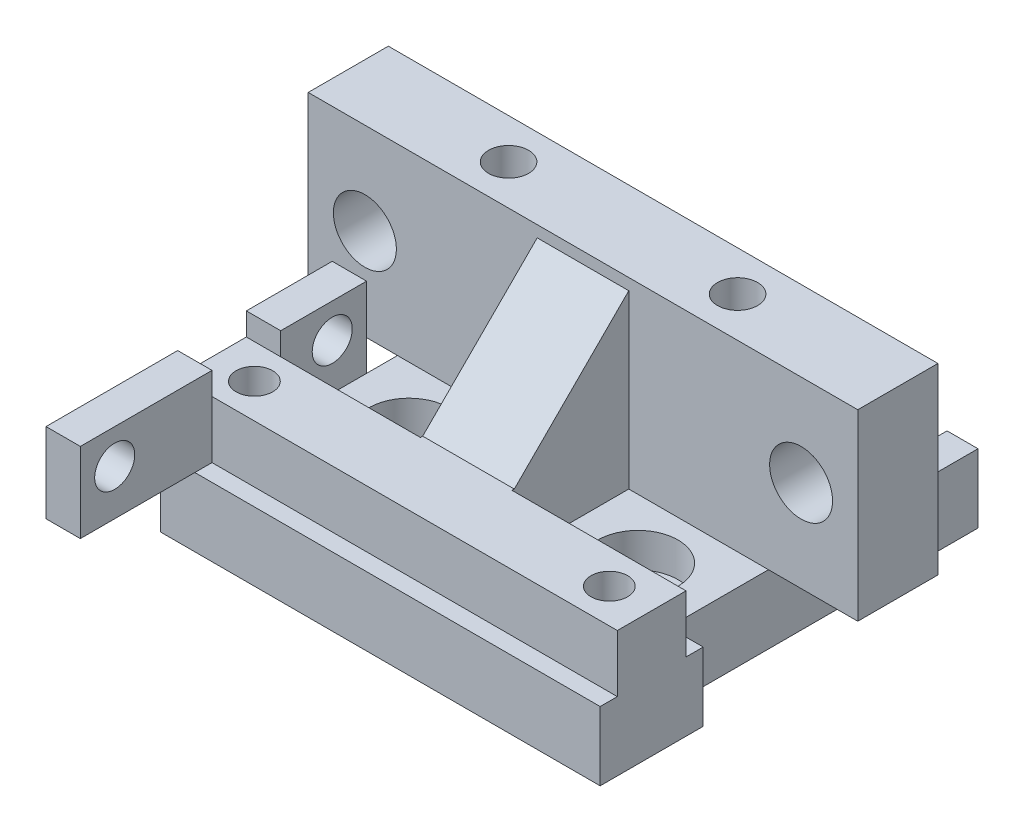
SolidWorks part; units mm, degrees
ref_plane "Спереди" through (0, 0, 0) normal (0, 0, 1) x (1, 0, 0)
ref_plane "Сверху" through (0, 0, 0) normal (0, 1, 0) x (1, 0, 0)
ref_plane "Справа" through (0, 0, 0) normal (1, 0, 0) x (0, 0, -1)
sketch "Эскиз1" plane through (0, 0, 0) normal (0, 1, 0) x (1, 0, 0)
  line L0 (16.2, 27) -> (16.2, 0) construction
  line L2 (0, 0) -> (0, 27)
  line L3 (0, 27) -> (32.4, 27)
  line L4 (32.4, 0) -> (32.4, 27)
  line L5 (0, 13.5) -> (32.4, 13.5) construction
  line L6 (0, 0) -> (-3, 0)
  line L7 (35.4, 0) -> (32.4, 0)
  line L8 (35.4, 0) -> (35.4, -9)
  line L9 (35.4, -9) -> (-3, -9)
  line L10 (-3, 0) -> (-3, -9)
  circle A0 centre (6.2, 23.5) radius 1.6
  circle A1 centre (26.2, 23.5) radius 1.6
  circle A2 centre (6.2, 3.5) radius 1.6
  circle A3 centre (26.2, 3.5) radius 1.6
  circle A4 centre (31.7, -4.5) radius 1.6
  circle A5 centre (0.7, -4.5) radius 1.6
  dimension "D3" = 3.2
  dimension "D6" = 10
  dimension "D12" = 3.2
  dimension "D1" = 32.4
  dimension "D2" = 27
  dimension "D4" = 10
  dimension "D5" = 10
  dimension "D7" = 10
  dimension "D8" = 10
  dimension "D9" = 10
  dimension "D10" = 10
  dimension "D11" = 10
  dimension "D13" = 15.5
  dimension "D14" = 15.5
  dimension "D15" = 8
  dimension "D16" = 8
  dimension "D17" = 3
  dimension "D18" = 3
  dimension "D19" = 4.5
extrude "Бобышка-Вытянуть1" add sketch "Эскиз1" along normal blind 6
sketch "Эскиз2" plane through (0, 6, 0) normal (0, 1, 0) x (1, 0, 0)
  line L7 (29.7, 23.5) -> (29.7, 27)
  line L8 (32.4, 27) -> (0, 27) construction
  line L9 (29.7, 27) -> (22.7, 27)
  line L10 (22.7, 27) -> (22.7, 23.5)
  line L11 (9.7, 23.5) -> (9.7, 27)
  line L12 (9.7, 27) -> (2.7, 27)
  line L13 (2.7, 27) -> (2.7, 23.5)
  arc A2 (22.7, 23.5) -> (29.7, 23.5) centre (26.2, 23.5) ccw
  arc A3 (2.7, 23.5) -> (9.7, 23.5) centre (6.2, 23.5) ccw
  circle A4 centre (26.2, 3.5) radius 3.5
  circle A6 centre (6.2, 3.5) radius 3.5
  dimension "D1" = 7
extrude "Вырез-Вытянуть1" cut sketch "Эскиз2" against normal blind 3
sketch "Эскиз3" plane through (0, 6, 0) normal (0, 1, 0) x (1, 0, 0)
  line L0 (-3, -9) -> (35.4, -9) construction
  line L1 (40.2, 15.7) -> (-7.8, 15.7)
  line L2 (40.2, 15.7) -> (40.2, 8.7)
  line L3 (40.2, 8.7) -> (-7.8, 8.7)
  line L4 (-7.8, 15.7) -> (-7.8, 8.7)
  line L6 (22.7, 27) -> (9.7, 27) construction
  line L7 (16.2, -9) -> (16.2, 27) construction
  point P6 (16.2, 0)
  point P7 (16.2, -9)
  point P10 (0, 0)
  point P12 (16.2, 0)
  dimension "D1" = 11.3
  dimension "D2" = 7
  dimension "D3" = 48
  dimension "D4" = 24
extrude "Бобышка-Вытянуть2" add sketch "Эскиз3" along normal blind 16
sketch "Эскиз5" plane through (0, 0, -15.7) normal (0, 0, -1) x (-1, 0, 0)
  line L0 (-40.2, 14) -> (7.8, 14) construction
  line L1 (-40.2, 22) -> (-40.2, 6) construction
  line L2 (7.8, 22) -> (7.8, 6) construction
  line L3 (-16.2, 22) -> (-16.2, 6) construction
  line L4 (-40.2, 22) -> (7.8, 22) construction
  line L5 (-32.4, 6) -> (0, 6) construction
  circle A0 centre (-35.25, 14) radius 2.75
  circle A1 centre (2.85, 14) radius 2.75
  dimension "D1" = 5.5
  dimension "D2" = 19.05
  dimension "D3" = 19.05
sketch "Эскиз6" plane through (0, 6, 0) normal (0, 1, 0) x (1, 0, 0)
  line L0 (35.4, -9) -> (35.4, 0) construction
  line L1 (35.4, -7.5) -> (-3, -7.5)
  line L2 (35.4, -7.5) -> (35.4, -1.5)
  line L3 (35.4, -1.5) -> (20.2, -1.5)
  line L4 (-3, -7.5) -> (-3, -1.5)
  line L5 (-3, 0) -> (-3, -9) construction
  line L6 (-3, -9) -> (35.4, -9) construction
  line L7 (35.4, 0) -> (32.4, 0) construction
  line L8 (16.2, -9) -> (16.2, 8.7) construction
  line L9 (0, 8.7) -> (32.4, 8.7) construction
  line L10 (12.2, -1.5) -> (-3, -1.5)
  line L12 (20.2, -1.5) -> (20.2, 8.7)
  line L13 (20.2, 8.7) -> (12.2, 8.7)
  line L14 (12.2, -1.5) -> (12.2, 8.7)
  circle A0 centre (31.7, -4.5) radius 1.6
  circle A1 centre (0.7, -4.5) radius 1.6
  dimension "D1" = 1.5
  dimension "D2" = 1.5
  dimension "D3" = 8
  dimension "D4" = 4
extrude "Вырез-Вытянуть2" cut sketch "Эскиз5" against normal up to surface (7 mm away) up to face at (16.2, 11.3333, -8.7)
extrude "Бобышка-Вытянуть3" add sketch "Эскиз6" along normal blind 5
sketch "Эскиз7" plane through (0, 0, 0) normal (-1, 0, 0) x (0, 0, 1)
  line L0 (-27, 0) -> (0, 0) construction
  line L2 (9, 6) -> (9, 0) construction
  line L3 (7.5, 12.9764) -> (19, 12.9764)
  line L4 (-6, 0) -> (9, 0)
  line L5 (-6, 0) -> (-6, 12.9764)
  line L6 (-6, 12.9764) -> (1.5, 12.9764)
  line L7 (19, 6) -> (19, 12.9764)
  line L9 (9, 0) -> (9, 6)
  line L10 (9, 6) -> (19, 6)
  line L12 (1.5, 11) -> (7.5, 11)
  line L13 (1.5, 11) -> (1.5, 12.9764)
  line L15 (7.5, 11) -> (7.5, 12.9764)
  circle A0 centre (-3, 10) radius 1.75
  circle A1 centre (16, 9.9764) radius 1.75
  dimension "D1" = 3.5
  dimension "D2" = 10
  dimension "D3" = 12
  dimension "D4" = 19
  dimension "D5" = 3
  dimension "D6" = 3
  dimension "D7" = 3
extrude "Бобышка-Вытянуть4" add sketch "Эскиз7" along normal blind 3
chamfer "Фаска1" distance 10 angle 45 1 edges at (16.2, 11, -8.7)
sketch "Эскиз8" plane through (0, 11, 0) normal (0, 1, 0) x (1, 0, 0)
  circle A0 centre (0.7, -4.5) radius 1.6
  dimension "D1" = 3.2
extrude "Вырез-Вытянуть3" cut sketch "Эскиз8" against normal up to surface (11 mm away) up to face at (1.15, 0, 4.5)
sketch "Эскиз9" plane through (0, 22, 0) normal (0, 1, 0) x (1, 0, 0)
  line L0 (40.2, 12.2) -> (-7.8, 12.2) construction
  line L1 (40.2, 8.7) -> (40.2, 15.7) construction
  line L2 (-7.8, 15.7) -> (-7.8, 8.7) construction
  line L3 (16.2, 8.7) -> (16.2, 15.7) construction
  line L4 (-7.8, 8.7) -> (40.2, 8.7) construction
  line L5 (32.4, 15.7) -> (0, 15.7) construction
  circle A0 centre (26.2, 12.2) radius 1.75
  circle A1 centre (6.2, 12.2) radius 1.75
  dimension "D1" = 3.5
  dimension "D2" = 10
  dimension "D3" = 10
extrude "Вырез-Вытянуть4" cut sketch "Эскиз9" against normal blind 7
